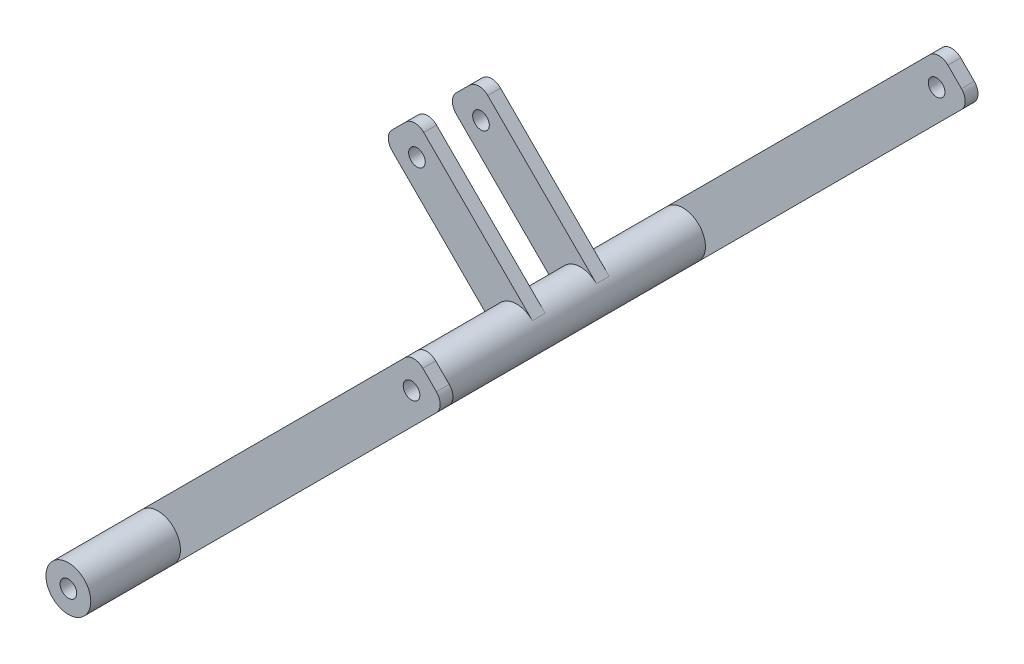
SolidWorks part; units mm, degrees
ref_plane "Front Plane" through (0, 0, 0) normal (0, 0, 1) x (1, 0, 0)
ref_plane "Top Plane" through (0, 0, 0) normal (0, 1, 0) x (1, 0, 0)
ref_plane "Right Plane" through (0, 0, 0) normal (1, 0, 0) x (0, 0, -1)
sketch "Sketch1" plane through (0, 0, 0) normal (0, 0, 1) x (1, 0, 0)
  circle A0 centre (0, 0) radius 17.5
  circle A1 centre (0, 0) radius 6.5
  dimension "D1" = 35
  dimension "D2" = 13
extrude "Boss-Extrude1" add sketch "Sketch1" along normal mid plane 560
ref_plane "Plane1" through (0, 0, 210) normal (0, 0, 1) x (1, 0, 0)
sketch "Sketch2" plane through (0, 0, 210) normal (0, 0, 1) x (1, 0, 0)
  line L0 (-12.3744, 12.3744) -> (192.6866, 217.4353)
  line L1 (206.8287, 217.4353) -> (217.4353, 206.8287)
  line L2 (217.4353, 192.6866) -> (12.3744, -12.3744)
  line L3 (0, 17.5) -> (-154.2118, 17.5) construction
  line L4 (212.132, 212.132) -> (197.9899, 197.9899) construction
  circle A0 centre (0, 0) radius 17.5 construction
  arc A1 (12.3744, -12.3744) -> (-12.3744, 12.3744) centre (0, 0) ccw
  circle A2 centre (197.9899, 197.9899) radius 6.5
  arc A3 (217.4353, 206.8287) -> (217.4353, 192.6866) centre (210.3643, 199.7577) cw
  arc A4 (206.8287, 217.4353) -> (192.6866, 217.4353) centre (199.7577, 210.3643) ccw
  point P13 (224.5064, 199.7577)
  point P16 (199.7577, 224.5064)
  dimension "D4" = 13
  dimension "D6" = 10
  dimension "D1" = 35
  dimension "D2" = 300
  dimension "D3" = 135
  dimension "D5" = 20
extrude "Boss-Extrude2" add sketch "Sketch2" against normal blind 10
mirror "Mirror1" about plane through (0, 0, 0) normal (0, 0, 1) of "Boss-Extrude2"
ref_plane "Plane2" through (0, 0, -120) normal (0, 0, 1) x (1, 0, 0)
sketch "Sketch3" plane through (0, 0, -120) normal (0, 0, 1) x (1, 0, 0)
  line L0 (0, 17.5) -> (240.4529, 17.5) construction
  line L1 (12.3744, 12.3744) -> (-72.4784, 97.2272)
  line L2 (-86.6206, 97.2272) -> (-97.2272, 86.6206)
  line L3 (-97.2272, 72.4784) -> (-12.3744, -12.3744)
  line L4 (-91.9239, 91.9239) -> (-77.7817, 77.7817) construction
  arc A0 (12.3744, -12.3744) -> (-12.3744, 12.3744) centre (0, 0) ccw construction
  circle A1 centre (0, 0) radius 17.5 construction
  arc A2 (12.3744, 12.3744) -> (-12.3744, -12.3744) centre (0, 0) ccw
  arc A3 (-72.4784, 97.2272) -> (-86.6206, 97.2272) centre (-79.5495, 90.1561) ccw
  arc A4 (-97.2272, 86.6206) -> (-97.2272, 72.4784) centre (-90.1561, 79.5495) ccw
  circle A5 centre (-77.7817, 77.7817) radius 6.5
  point P13 (-79.5495, 104.2983)
  point P16 (-104.2983, 79.5495)
  dimension "D4" = 10
  dimension "D5" = 13
  dimension "D1" = 35
  dimension "D2" = 135
  dimension "D3" = 130
  dimension "D6" = 20
extrude "Boss-Extrude3" add sketch "Sketch3" against normal blind 10 separate body
ref_plane "Plane3" through (0, 0, -100) normal (0, 0, -1) x (-1, 0, 0)
mirror "Mirror2" about plane through (0, 0, -100) normal (0, 0, -1) of bodies 104
